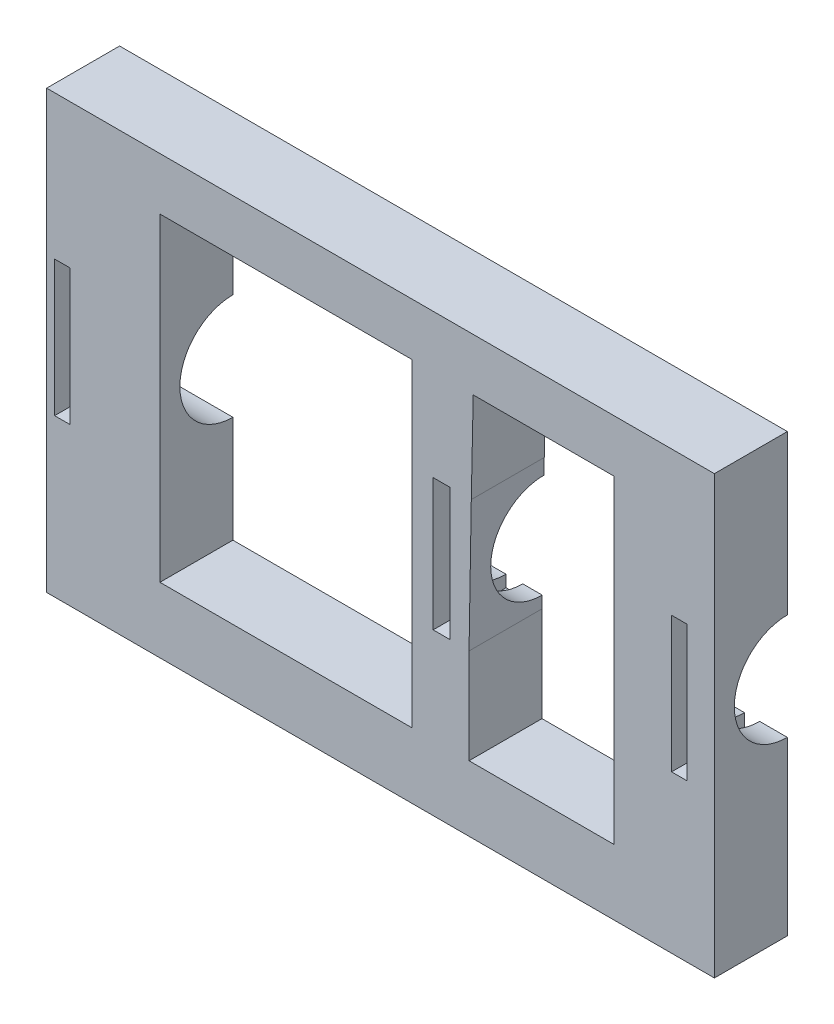
SolidWorks part; units mm, degrees
ref_plane "Front Plane" through (0, 0, 0) normal (0, 0, 1) x (1, 0, 0)
ref_plane "Top Plane" through (0, 0, 0) normal (0, 1, 0) x (1, 0, 0)
ref_plane "Right Plane" through (0, 0, 0) normal (1, 0, 0) x (0, 0, -1)
sketch "Sketch1" plane through (0, 0, 0) normal (0, 1, 0) x (1, 0, 0)
  line L3 (3.9498, 3.2101) -> (3.9498, 17.1069)
  line L4 (5.423, 3.2101) -> (5.423, 17.1069)
  line L5 (3.9498, 17.1069) -> (0, 17.1069)
  line L6 (0, 17.1069) -> (0, 0)
  line L7 (3.9498, 3.2101) -> (5.423, 3.2101)
  line L8 (10.9894, 3.2101) -> (10.9894, 0)
  line L9 (0, 0) -> (0, -3.1783)
  line L10 (0, -3.1783) -> (66.04, -3.1783)
  line L11 (5.423, 17.1069) -> (10.9894, 17.1069)
  line L12 (10.9894, 17.1069) -> (10.9894, 3.2101)
  line L13 (10.9894, 0) -> (55.0506, 0)
  line L15 (55.0506, 17.1069) -> (55.0506, 3.2101)
  line L16 (60.617, 17.1069) -> (55.0506, 17.1069)
  line L17 (66.04, 0) -> (66.04, -3.1783)
  line L18 (55.0506, 3.2101) -> (55.0506, 0)
  line L19 (62.0902, 3.2101) -> (60.617, 3.2101)
  line L20 (66.04, 17.1069) -> (66.04, 0)
  line L21 (62.0902, 17.1069) -> (66.04, 17.1069)
  line L22 (60.617, 3.2101) -> (60.617, 17.1069)
  line L23 (62.0902, 3.2101) -> (62.0902, 17.1069)
extrude "Boss-Extrude1" add sketch "Sketch1" along normal blind 13.1572
sketch "Sketch2" plane through (0, 13.1572, 0) normal (0, 1, 0) x (1, 0, 0)
  line L0 (10.9894, 17.1069) -> (0, 17.1069)
  line L1 (0, 17.1069) -> (0, -3.1783)
  line L2 (0, -3.1783) -> (66.04, -3.1783)
  line L3 (0, -3.1783) -> (66.04, -3.1783) construction
  line L4 (66.04, -3.1783) -> (66.04, 17.1069)
  line L5 (66.04, 17.1069) -> (55.0506, 17.1069)
  line L6 (55.0506, 17.1069) -> (55.0506, -0.2263)
  line L7 (55.0506, -0.2263) -> (10.9894, 0)
  line L8 (10.9894, 0) -> (10.9894, 17.1069)
extrude "Boss-Extrude2" add sketch "Sketch2" along normal blind 8.89
sketch "Sketch3" plane through (0, 22.0472, 0) normal (0, 1, 0) x (1, 0, 0)
  line L0 (0, -3.1783) -> (66.04, -3.1783)
  line L1 (0, -3.1783) -> (66.04, -3.1783) construction
  line L2 (66.04, -3.1783) -> (66.04, 17.1069)
  line L3 (66.04, 17.1069) -> (0, 17.1069)
  line L4 (0, 17.1069) -> (0, -3.1783)
  point P9 (66.04, -3.1783)
extrude "Boss-Extrude3" add sketch "Sketch3" along normal blind 5.08
sketch "Sketch4" plane through (0, 0, 0) normal (0, -1, 0) x (1, 0, 0)
  line L0 (66.04, -17.1069) -> (55.0506, -17.1069)
  line L1 (55.0506, -17.1069) -> (55.0506, 0)
  line L2 (55.0506, 0) -> (10.9894, 0)
  line L3 (10.9894, 0) -> (10.9894, -17.1069)
  line L4 (10.9894, -17.1069) -> (0, -17.1069)
  line L5 (0, -17.1069) -> (0, 3.1783)
  line L6 (0, 3.1783) -> (66.04, 3.1783)
  line L7 (66.04, 3.1783) -> (66.04, -17.1069)
extrude "Boss-Extrude4" add sketch "Sketch4" along normal blind 8.89
sketch "Sketch6" plane through (55.0506, 0, 0) normal (-1, 0, 0) x (0, 0, 1)
  line L0 (-17.1069, 22.0472) -> (-17.1069, -8.89) construction
  circle A0 centre (-17.1069, 6.5786) radius 5.1435
extrude "Cut-Extrude1" cut sketch "Sketch6" against normal through all both and the other way through all
sketch "Sketch7" plane through (0, -8.89, 0) normal (0, -1, 0) x (1, 0, 0)
  line L1 (66.04, -17.1069) -> (0, -17.1069)
  line L2 (66.04, -17.1069) -> (66.04, 3.1783)
  line L3 (66.04, 3.1783) -> (0, 3.1783)
  line L4 (0, -17.1069) -> (0, 3.1783)
extrude "Boss-Extrude5" add sketch "Sketch7" along normal blind 25.4
sketch "Sketch9" plane through (0, 0, -17.1069) normal (0, 0, -1) x (-1, 0, 0)
  line L1 (-39.1063, 0.3654) -> (-39.1063, 13.1572)
  line L2 (-39.1063, 13.1572) -> (-37.4909, 13.1572)
  line L3 (-37.4909, 13.1572) -> (-37.4909, 0.3654)
  line L4 (-37.4909, 0.3654) -> (-39.1063, 0.3654)
  line L6 (-41.1891, 13.1572) -> (-40.9712, 0.3337)
  line L7 (-40.9712, 0.3337) -> (-40.9712, -8.89)
  line L8 (-10.9894, -8.89) -> (-55.0506, -8.89) construction
  line L9 (-40.9712, -8.89) -> (-37.4909, -8.89)
  line L10 (-37.4909, -8.89) -> (-35.4589, -8.89)
  line L11 (-35.4589, -8.89) -> (-35.4589, 13.1572)
  line L13 (-35.4589, -8.89) -> (-35.4589, 22.0472)
  line L14 (-55.0506, 22.0472) -> (-10.9894, 22.0472) construction
  line L15 (-35.4589, 22.0472) -> (-41.3759, 22.0472)
  line L16 (-41.3759, 22.0472) -> (-41.1891, 13.1572)
  line M28 (-10.9894, -8.89) -> (-55.0506, -8.89)
extrude "Boss-Extrude6" add sketch "Sketch9" against normal blind 19.05 contours L15 L16 L6 L7 L11 L13 L3 L4 L1 L2 M28
sketch "Sketch10" plane through (35.4589, 0, 0) normal (-1, 0, 0) x (0, 0, 1)
  line L0 (-17.1069, -8.89) -> (-17.1069, 22.0472) construction
  circle A0 centre (-17.1069, 6.5786) radius 5.08
extrude "Cut-Extrude2" cut sketch "Sketch10" against normal blind 15.24
sketch "Sketch12" plane through (66.04, 0, 0) normal (1, 0, 0) x (0, 0, -1)
  line L0 (17.1069, 27.1272) -> (17.1069, 11.7221)
  line L1 (17.1069, 27.1272) -> (-3.5261, 27.1272)
  line L2 (-3.5261, 27.1272) -> (-3.1783, -34.29)
  line L3 (-3.1783, 27.1272) -> (-3.1783, -34.29) construction
  line L4 (17.1069, -34.29) -> (-3.1783, -34.29) construction
  line L5 (-3.1783, -34.29) -> (17.1069, -34.29)
  line L6 (17.1069, -34.29) -> (17.1069, 1.4351)
  line L7 (17.1069, 11.7221) -> (17.1069, 1.4351)
extrude "Cut-Extrude3" cut sketch "Sketch12" against normal blind 1.27
sketch "Sketch14" plane through (0, 0, -17.1069) normal (0, 0, -1) x (-1, 0, 0)
  line L1 (-5.423, 13.1572) -> (-3.9498, 13.1572)
  line L2 (-5.423, 13.1572) -> (-5.423, 0)
  line L3 (-5.423, 0) -> (-3.9498, 0)
  line L4 (-3.9498, 13.1572) -> (-3.9498, 0)
  line L5 (-0.7748, 13.1572) -> (-0.7748, 0)
  line L6 (-0.7748, 0) -> (-2.248, 0)
  line L7 (-2.248, 0) -> (-2.248, 13.1572)
  line L8 (-2.248, 13.1572) -> (-0.7748, 13.1572)
extrude "Cut-Extrude4" cut sketch "Sketch14" against normal blind 15.24
sketch "Sketch15" plane through (0, -34.29, 0) normal (0, -1, 0) x (1, 0, 0)
  line L1 (64.77, 3.1783) -> (0, 3.1783)
  line L2 (64.77, 3.1783) -> (64.77, -17.1069)
  line L3 (64.77, -17.1069) -> (0, -17.1069)
  line L4 (0, 3.1783) -> (0, -17.1069)
extrude "Cut-Extrude5" cut sketch "Sketch15" against normal blind 19.05
sketch "Sketch16" plane through (5.423, 0, 0) normal (-1, 0, 0) x (0, 0, 1)
  line L0 (-17.1069, 13.1572) -> (6.0758, 13.1572)
  line L1 (6.0758, 13.1572) -> (6.0758, 0)
  line L2 (6.0758, 0) -> (-17.1069, 0)
  line L3 (-17.1069, 0) -> (-17.1069, 1.4351)
  line L5 (-17.1069, 11.7221) -> (-17.1069, 13.1572)
  arc A0 (-17.1069, 1.4351) -> (-17.1069, 11.7221) centre (-17.1069, 6.5786) ccw construction
  arc A1 (-17.1069, 1.4351) -> (-17.1069, 11.7221) centre (-17.1069, 6.5786) ccw
extrude "Boss-Extrude7" add sketch "Sketch16" along normal blind 1.4986
sketch "Sketch17" plane through (0, 0, 3.1783) normal (0, 0, 1) x (1, 0, 0)
  line L1 (0, 27.1272) -> (64.77, 27.1272)
  line L2 (0, 27.1272) -> (0, -15.24)
  line L3 (0, -15.24) -> (64.77, -15.24)
  line L4 (64.77, 27.1272) -> (64.77, -15.24)
extrude "Cut-Extrude7" cut sketch "Sketch17" against normal blind 13.208
